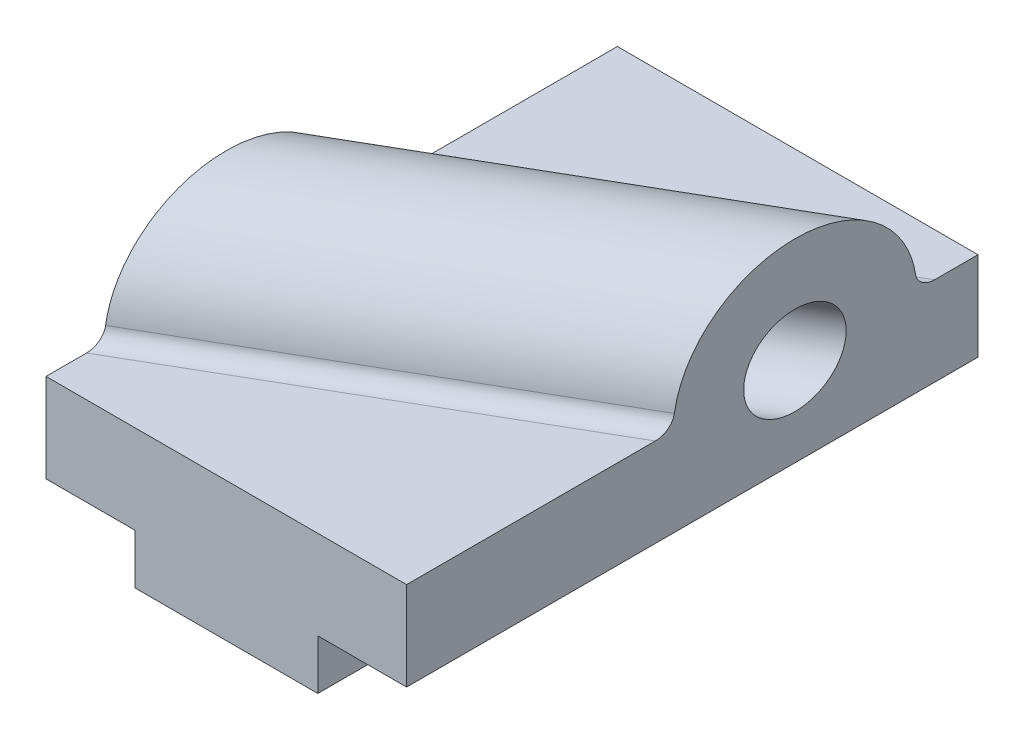
SolidWorks part; units mm, degrees
ref_plane "Front Plane" through (0, 0, 0) normal (0, 0, 1) x (1, 0, 0)
ref_plane "Top Plane" through (0, 0, 0) normal (0, 1, 0) x (1, 0, 0)
ref_plane "Right Plane" through (0, 0, 0) normal (1, 0, 0) x (0, 0, -1)
sketch "Sketch2" plane through (0, 0, 0) normal (0, 0, 1) x (1, 0, 0)
  line L0 (-14.5294, -4.3824) -> (-14.5294, -13.3824)
  line L1 (-30.5294, 11.6176) -> (34.4706, 11.6176)
  line L2 (-30.5294, 11.6176) -> (-30.5294, -4.3824)
  line L3 (-30.5294, -4.3824) -> (-14.5294, -4.3824)
  line L4 (34.4706, 11.6176) -> (34.4706, -4.3824)
  line L5 (-14.5294, -13.3824) -> (18.4706, -13.3824)
  line L6 (18.4706, -13.3824) -> (18.4706, -4.3824)
  line L7 (18.4706, -4.3824) -> (34.4706, -4.3824)
  dimension "D1" = 65
  dimension "D2" = 33
  dimension "D3" = 16
  dimension "D4" = 9
  dimension "D5" = 25
extrude "Boss-Extrude1" add sketch "Sketch2" along normal blind 103
ref_plane "Plane1" through (-18.7474, 0, 10.8238) normal (0.866, 0, -0.5) x (0, 1, 0)
ref_point "Point1" parameters "D1"=33
sketch "Sketch3" plane through (-18.7474, 0, 10.8238) normal (0.866, 0, -0.5) x (0, 1, 0)
  line L0 (11.6176, 64.8141) -> (11.6176, 26.8141)
  arc A0 (11.6176, 26.8141) -> (11.6176, 64.8141) centre (11.6176, 45.8141) ccw
  dimension "D1" = 38
extrude "Boss-Extrude4" add sketch "Sketch3" along normal up to surface and the other way up to surface up to face at (34.4706, 3.6176, 51.5) other way up to face at (-30.5294, 3.6176, 51.5)
sketch "Sketch4" plane through (-18.7474, 0, 10.8238) normal (0.866, 0, -0.5) x (0, 1, 0)
  circle A0 centre (11.6176, 45.8141) radius 8
  dimension "D1" = 16
extrude "Cut-Extrude1" cut sketch "Sketch4" against normal through all both and the other way through all
fillet "Fillet1" radius 3 2 edges at (1.9706, 11.6176, 73.7032) (1.9706, 11.6176, 29.8246)
